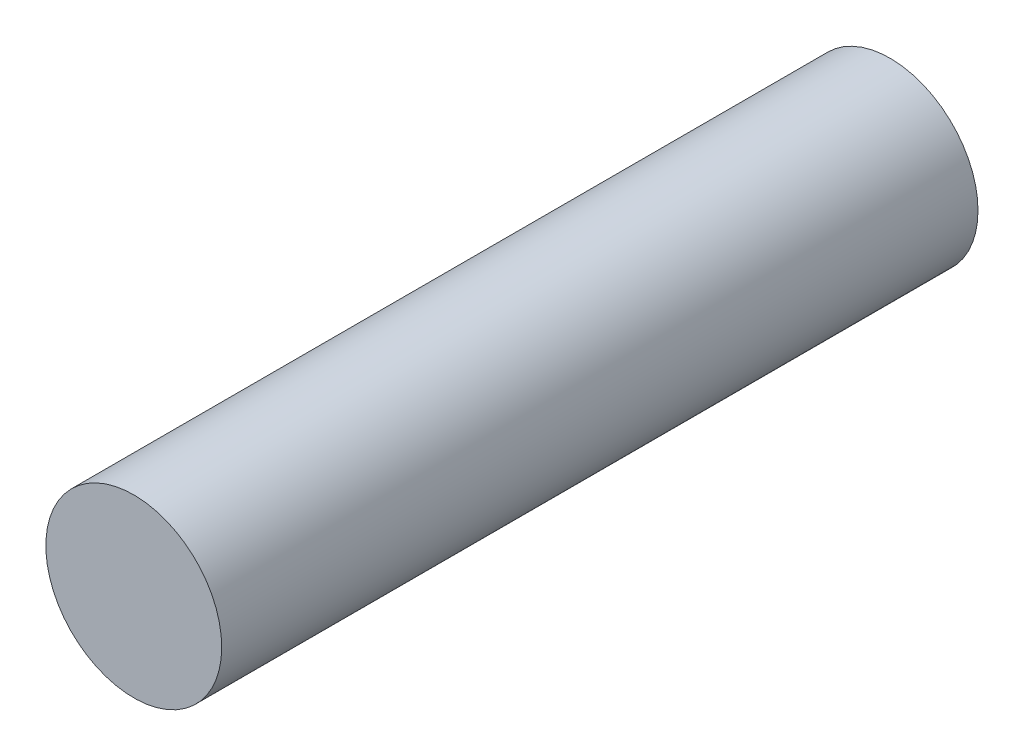
SolidWorks part; units mm, degrees
ref_plane "Front Plane" through (0, 0, 0) normal (0, 0, 1) x (1, 0, 0)
ref_plane "Top Plane" through (0, 0, 0) normal (0, 1, 0) x (1, 0, 0)
ref_plane "Right Plane" through (0, 0, 0) normal (1, 0, 0) x (0, 0, -1)
sketch "Sketch2" plane through (0, 0, 0) normal (0, 0, 1) x (1, 0, 0)
  circle A0 centre (0, 0) radius 5
extrude "Boss-Extrude1" add sketch "Sketch2" along normal blind 43
